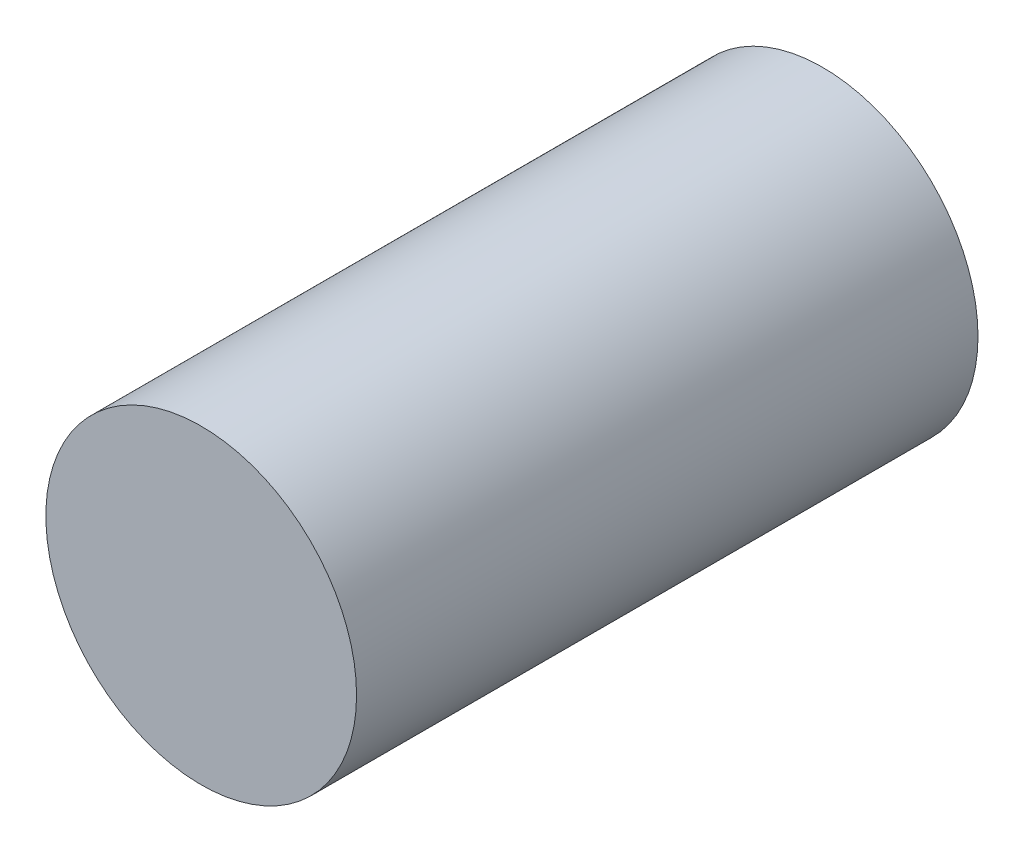
SolidWorks part; units mm, degrees
ref_plane "正面" through (0, 0, 0) normal (0, 0, 1) x (1, 0, 0)
ref_plane "平面" through (0, 0, 0) normal (0, 1, 0) x (1, 0, 0)
ref_plane "右側面" through (0, 0, 0) normal (1, 0, 0) x (0, 0, -1)
sketch "ｽｹｯﾁ1" plane through (0, 0, 0) normal (0, 0, 1) x (1, 0, 0)
  circle A0 centre (0, 0) radius 50
  dimension "D1" = 100
extrude "ﾎﾞｽ - 押し出し1" add sketch "ｽｹｯﾁ1" along normal blind 200
